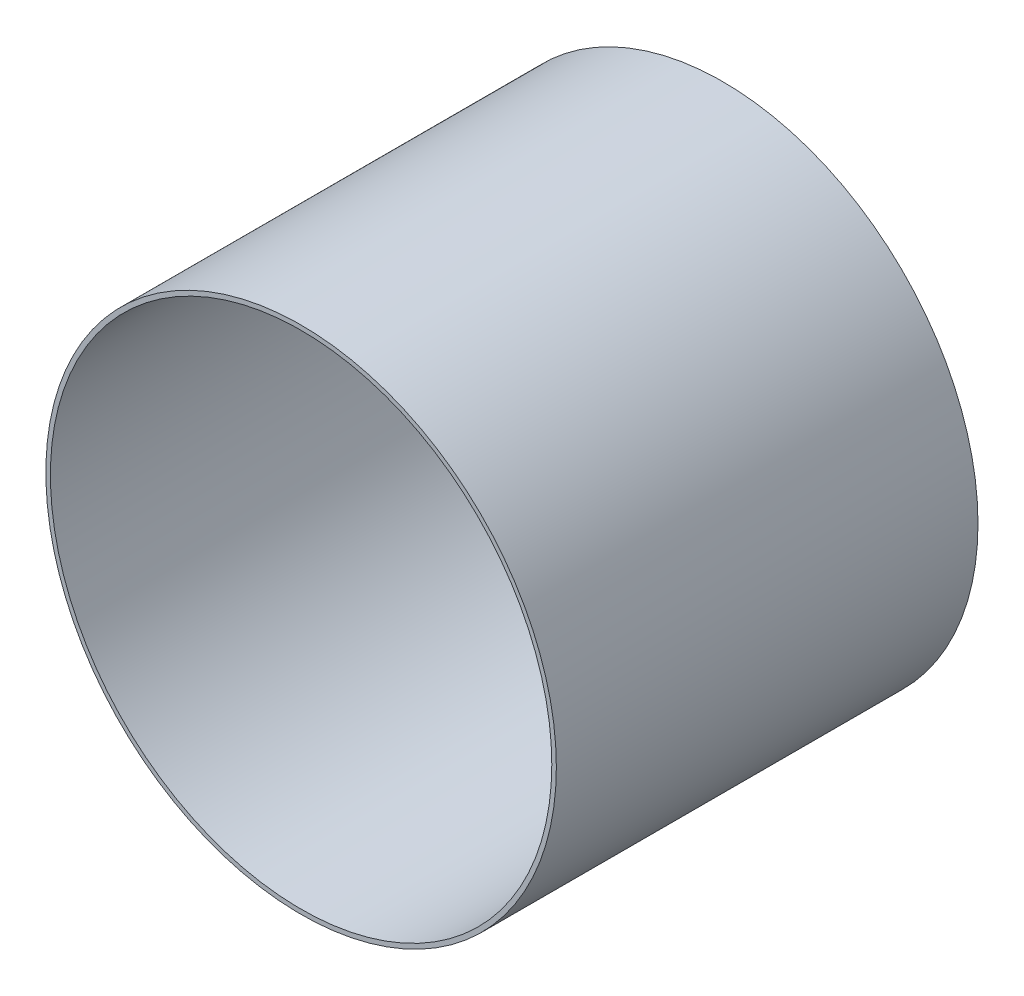
SolidWorks part; units mm, degrees
ref_plane "Front Plane" through (0, 0, 0) normal (0, 0, 1) x (1, 0, 0)
ref_plane "Top Plane" through (0, 0, 0) normal (0, 1, 0) x (1, 0, 0)
ref_plane "Right Plane" through (0, 0, 0) normal (1, 0, 0) x (0, 0, -1)
sketch "Sketch1" plane through (0, 0, 0) normal (0, 0, 1) x (1, 0, 0)
  circle A0 centre (0, 0) radius 69.85
  circle A1 centre (0, 0) radius 71.12
  dimension "D1" = 142.24
  dimension "D2" = 139.7
extrude "Extrude1" add sketch "Sketch1" along normal blind 117.475
